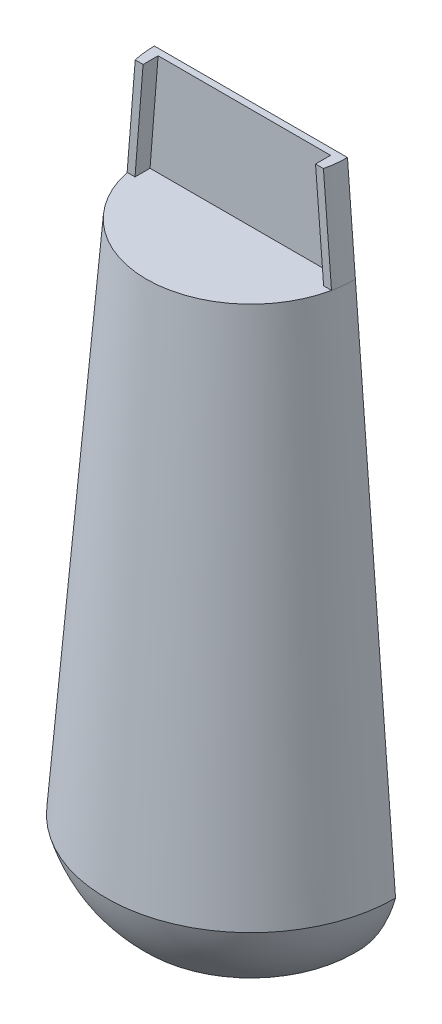
SolidWorks part; units mm, degrees
ref_plane "Front Plane" through (0, 0, 0) normal (0, 0, 1) x (1, 0, 0)
ref_plane "Top Plane" through (0, 0, 0) normal (0, 1, 0) x (1, 0, 0)
ref_plane "Right Plane" through (0, 0, 0) normal (1, 0, 0) x (0, 0, -1)
sketch "Sketch1" plane through (0, 0, 0) normal (0, 0, 1) x (1, 0, 0)
  line L0 (27.686, 0) -> (22.606, 0)
  line L1 (22.606, 0) -> (22.606, 1.8288)
  line L2 (28.829, 4.191) -> (22.606, 4.191)
  line L3 (22.606, 4.191) -> (22.606, 5.8928)
  line L4 (22.606, 5.8928) -> (30.607, 5.8928)
  line L5 (36.5429, 18.669) -> (0, 18.669)
  line L6 (0, 18.669) -> (0, 185.547)
  line L7 (0, 185.547) -> (26.0985, 185.547)
  line L8 (26.0985, 185.547) -> (39.0906, 18.669)
  line L9 (36.5429, 18.669) -> (35.5415, 31.5318) construction
  line L10 (27.686, 0) -> (-4.9317, -30.4165) construction
  line L11 (39.0906, 18.669) -> (57.9001, 81.973) construction
  line L12 (34.3825, 10.171) -> (26.8315, 1.6146) construction
  line L13 (30.8955, 5.835) -> (26.7625, 2.547) construction
  line L14 (22.606, 1.8288) -> (0, 1.8288) construction
  spline S0 degree 3 poles (27.686, 0) (33.0192, 4.9733) (36.7329, 10.7342) (39.0906, 18.669) knots 0 0 0 0 1 1 1 1
  spline S1 degree 3 poles (22.606, 1.8288) (25.0412, 1.8288) (27.1069, 2.821) (28.829, 4.191) knots 0 0 0 0 0.286843 0.286843 0.286843 0.286843
  spline S2 degree 2 poles (30.607, 5.8928) (35.3264, 11.2406) (36.5429, 18.669) knots 0.392904 0.392904 0.392904 1 1 1
  dimension "D1" = 185.547
  dimension "D2" = 39.0906
  dimension "D3" = 18.669
  dimension "D4" = 22.606
  dimension "D5" = 5.08
  dimension "D6" = 1.8288
  dimension "D7" = 2.3622
  dimension "D8" = 6.223
  dimension "D9" = 1.7018
  dimension "D10" = 8.001
  dimension "D11" = 26.0985
  dimension "D12" = 2.54
  dimension "D13" = 43
  dimension "D14" = 21
revolve "Revolve1" add sketch "Sketch1" angle 180 about L6
sketch "Sketch2" plane through (0, 185.547, 0) normal (0, 1, 0) x (1, 0, 0)
  line L0 (-23.3045, -1.778) -> (23.3045, -1.778)
  line L1 (23.3045, -1.778) -> (23.3045, -5.842)
  line L2 (23.3045, -5.842) -> (25.4362, -5.842)
  line L3 (25.4362, -5.842) -> (28.0363, -5.842)
  line L4 (-23.3045, -1.778) -> (-23.3045, -5.842)
  line L5 (-23.3045, -5.842) -> (-25.4362, -5.842)
  line L6 (-25.4362, -5.842) -> (-28.0363, -5.842)
  arc A1 (-26.0985, 0) -> (26.0985, 0) centre (0, 0) ccw construction
  arc A2 (-28.6385, 0) -> (28.6385, 0) centre (0, 0) ccw
  arc A3 (-28.0363, -5.842) -> (28.0363, -5.842) centre (0, 0) ccw
  point P6 (0, -1.778)
  dimension "D1" = 2.54
  dimension "D2" = 46.609
  dimension "D3" = 4.064
  dimension "D4" = 5.842
  dimension "D5" = 2.1317
sketch "Sketch3" plane through (0, 0, 0) normal (0, 0, 1) x (1, 0, 0)
  line L0 (-39.0906, 158.115) -> (39.0906, 158.115)
  dimension "D1" = 158.115
split line "Split Line1"
ref_plane "Plane1" through (0, 158.115, 0) normal (0, 1, 0) x (1, 0, 0)
sketch "Sketch4" plane through (0, 158.115, 0) normal (0, 1, 0) x (1, 0, 0)
  line L0 (-25.4914, -1.778) -> (25.4914, -1.778)
  line L1 (25.4914, -1.778) -> (25.4914, -5.842)
  line L2 (25.4914, -5.842) -> (27.6232, -5.842)
  line L3 (27.6232, -5.842) -> (30.2146, -5.842)
  line L4 (-25.4914, -1.778) -> (-25.4914, -5.842)
  line L5 (-25.4914, -5.842) -> (-27.6232, -5.842)
  line L6 (-27.6232, -5.842) -> (-30.2146, -5.842)
  arc A1 (-28.2342, 0) -> (28.2342, 0) centre (0, 0) ccw construction
  arc A2 (-30.7742, 0) -> (30.7742, 0) centre (0, 0) ccw
  arc A3 (-30.2146, -5.842) -> (30.2146, -5.842) centre (0, 0) ccw
  point P6 (0, -1.778)
  dimension "D2" = 4.064
  dimension "D3" = 5.842
  dimension "D4" = 2.1317
  dimension "D1" = 2.54
loft "Cut-Loft1" cut profiles "Sketch2", "Sketch4"
equation "\"D2@Sketch4\"= \"D3@Sketch2\""
equation "\"D3@Sketch4\"= \"D4@Sketch2\""
equation "\"D4@Sketch4\"= \"D5@Sketch2\""
